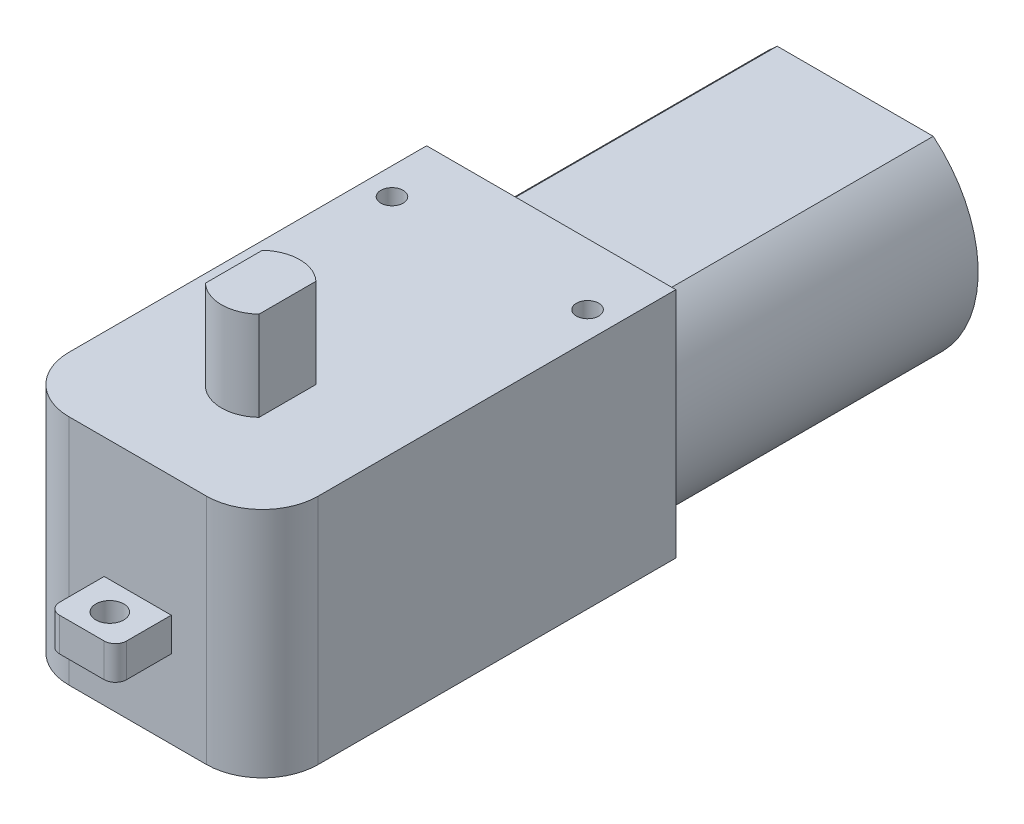
SolidWorks part; units mm, degrees
ref_plane "Front Plane" through (0, 0, 0) normal (0, 0, 1) x (1, 0, 0)
ref_plane "Top Plane" through (0, 0, 0) normal (0, 1, 0) x (1, 0, 0)
ref_plane "Right Plane" through (0, 0, 0) normal (1, 0, 0) x (0, 0, -1)
sketch "Sketch1" plane through (0, 0, 0) normal (0, 1, 0) x (1, 0, 0)
  line L0 (0, 0) -> (0, 50000) construction
  line L1 (-11.15, 0) -> (11.15, 0)
  line L2 (-11.15, 0) -> (-11.15, 37)
  line L3 (-11.15, 37) -> (11.15, 37)
  line L4 (11.15, 0) -> (11.15, 37)
  dimension "D1" = 37
  dimension "D2" = 22.3
extrude "Boss-Extrude1" add sketch "Sketch1" along normal blind 20.8
fillet "Fillet1" radius 5 2 edges at (11.15, 10.4, 0) (-11.15, 10.4, 0)
sketch "Sketch2" plane through (0, 0, -37) normal (0, 0, -1) x (-1, 0, 0)
  line L0 (0, 0) -> (0, 20.8) construction
  line L1 (-11.15, 0) -> (11.15, 0) construction
  line L2 (-11.15, 20.8) -> (11.15, 20.8) construction
  line L3 (-6.9821, 0) -> (6.9821, 0)
  line L4 (-6.9821, 0.5) -> (-6.9821, 50000.5) construction
  line L5 (-6.9821, 17) -> (6.9821, 17)
  line L6 (6.9821, 13.8713) -> (6.9821, -49986.1287) construction
  arc A0 (-6.9821, 0) -> (-6.9821, 17) centre (0, 8.5) cw
  arc A1 (6.9821, 0) -> (6.9821, 17) centre (0, 8.5) ccw
  dimension "D2" = 11
  dimension "D1" = 17
extrude "Boss-Extrude2" add sketch "Sketch2" along normal blind 27.2
sketch "Sketch3" plane through (0, 20.8, 0) normal (0, 1, 0) x (1, 0, 0)
  line L0 (0, 0) -> (0, 50000) construction
  line L1 (-6.15, 0) -> (6.15, 0) construction
  line L2 (16.2384, 11) -> (50016.2384, 11) construction
  circle A0 centre (0, 11) radius 3.5
  point P4 (0, 0)
  dimension "D2" = 7
  dimension "D1" = 11
extrude "Boss-Extrude3" add sketch "Sketch3" along normal blind 8
sketch "Sketch4" plane through (0, 28.8, 0) normal (0, 1, 0) x (1, 0, 0)
  line L0 (-2.4, 13.5475) -> (-2.4, 8.4525)
  line L1 (2.4, 13.5475) -> (2.4, 8.4525)
  line L2 (0, 10) -> (0, 50010) construction
  circle A0 centre (0, 11) radius 3.5 construction
  circle A1 centre (0, 11) radius 3.5 construction
  arc A2 (-2.4, 8.4525) -> (-2.4, 13.5475) centre (0, 11) cw
  arc A3 (2.4, 8.4525) -> (2.4, 13.5475) centre (0, 11) ccw
  dimension "D1" = 4.8
extrude "Cut-Extrude1" cut sketch "Sketch4" against normal up to surface (8 mm away) up to face at (0, 20.8, -13.6548)
sketch "Sketch5" plane through (0, 0, 0) normal (0, 0, 1) x (1, 0, 0)
  line L0 (0, 0) -> (0, 50000) construction
  line L1 (-6.15, 0) -> (6.15, 0) construction
  line L3 (-3, 10) -> (3, 10)
  line L4 (-3, 10) -> (-3, 7)
  line L5 (-3, 7) -> (3, 7)
  line L6 (3, 10) -> (3, 7)
  line L7 (-3, 10) -> (3, 7) construction
  line L8 (-3, 7) -> (3, 10) construction
  point P4 (0, 0)
  point P5 (0, 8.5)
  dimension "D1" = 7
  dimension "D2" = 3
  dimension "D3" = 6
extrude "Boss-Extrude4" add sketch "Sketch5" along normal blind 5
sketch "Sketch7" plane through (0, 10, 0) normal (0, 1, 0) x (1, 0, 0)
  line L0 (-3, -2.5) -> (3, -2.5) construction
  line L1 (-3, -5) -> (-3, 0) construction
  line L2 (3, -5) -> (3, 0) construction
  line L3 (0, -5) -> (0, 0) construction
  line L4 (3, -5) -> (-3, -5) construction
  line L5 (3, 0) -> (-3, 0) construction
  circle A0 centre (0, -2.5) radius 1.25
  dimension "D1" = 2.5
extrude "Cut-Extrude2" cut sketch "Sketch7" against normal up to next
fillet "Fillet2" radius 1 2 edges at (3, 8.5, 5) (-3, 8.5, 5)
hole_wizard "Ø2.0mm Dowel Hole1" positions "Sketch9" profile "Sketch8" hole size "Ø2.0" standard "ISO" end condition through all
sketch "Sketch9" plane through (0, 20.8, 0) normal (0, 1, 0) x (1, 0, 0)
  line L0 (0, 0) -> (0, 50000) construction
  line L1 (-6.15, 0) -> (6.15, 0) construction
  line L2 (-1.3451, 31.5) -> (49998.6549, 31.5) construction
  line L3 (11.15, 37) -> (-11.15, 37) construction
  point P0 (-8.75, 31.5)
  point P2 (8.75, 31.5)
  point P9 (0, 0)
  dimension "D1" = 17.5
  dimension "D2" = 5.5
sketch "Sketch8" plane through (-8.75, 20.8, -31.5) normal (1, 0, 0) x (0, 0, 1)
  line L0 (0, 0) -> (0, 20.8)
  line L1 (0, 20.8) -> (1, 20.8)
  line L2 (1, 20.8) -> (1, 0)
  line L5 (1, 0) -> (0, 0)
  line L11 (0, -6.35) -> (0, 107.95) construction
  dimension "Thru Hole Dia." = 2
  dimension "Thru Hole Depth" = 20.8
sketch "Sketch10" plane through (0, 0, 0) normal (0, -1, 0) x (1, 0, 0)
  line L0 (0, 0) -> (0, -50000) construction
  line L1 (6.9821, -64.2) -> (-6.9821, -64.2) construction
  line L2 (-4, -41) -> (4, -41)
  line L3 (-4, -41) -> (-4, -64.2)
  line L4 (-4, -64.2) -> (4, -64.2)
  line L5 (4, -41) -> (4, -64.2)
  line L6 (-6.9821, -37) -> (-11.15, -37) construction
  dimension "D1" = 8
  dimension "D2" = 4
extrude "Boss-Extrude5" add sketch "Sketch10" along normal blind 2.5
sketch "Sketch11" plane through (0, 0, 0) normal (0, -1, 0) x (1, 0, 0)
  circle A0 centre (0, -11) radius 4.5
  dimension "D1" = 9
extrude "Boss-Extrude6" add sketch "Sketch11" along normal blind 0.9
